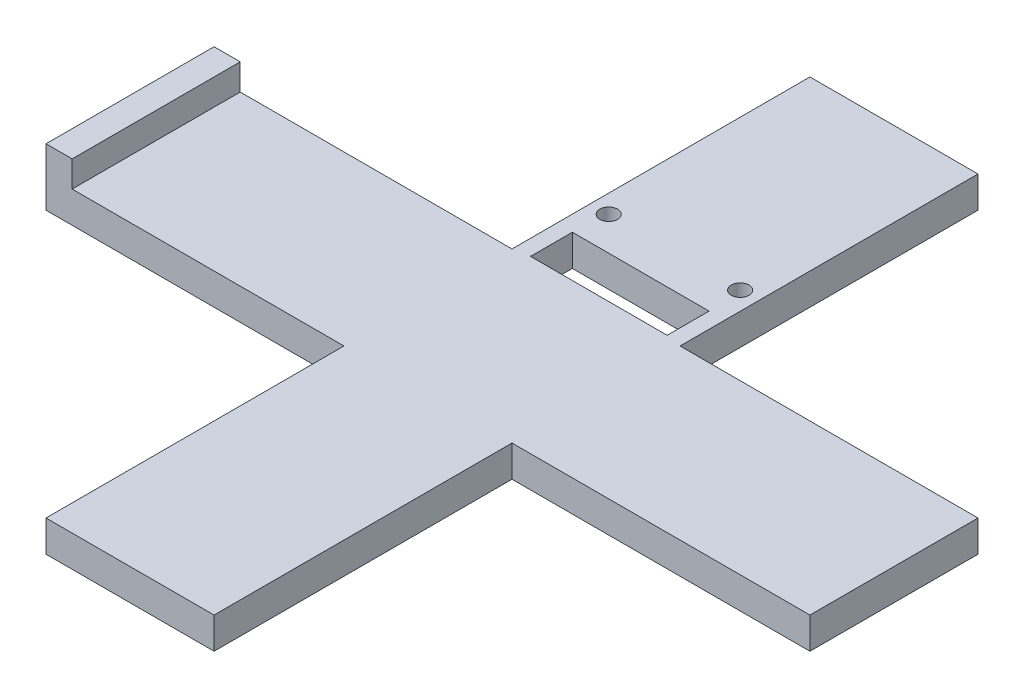
SolidWorks part; units mm, degrees
ref_plane "Front Plane" through (0, 0, 0) normal (0, 0, 1) x (1, 0, 0)
ref_plane "Top Plane" through (0, 0, 0) normal (0, 1, 0) x (1, 0, 0)
ref_plane "Right Plane" through (0, 0, 0) normal (1, 0, 0) x (0, 0, -1)
sketch "Sketch21" plane through (0, 0, 0) normal (0, 1, 0) x (1, 0, 0)
  line L22 (0, 73) -> (-16.06, 73)
  line L23 (-16.06, 73) -> (-16.06, 16.06)
  line L24 (-16.06, 16.06) -> (-73, 16.06)
  line L25 (-73, -16.06) -> (-16.06, -16.06)
  line L26 (-16.06, -16.06) -> (-16.06, -73)
  line L27 (-16.06, -73) -> (0, -73)
  line L28 (0, -73) -> (16.06, -73)
  line L29 (16.06, -73) -> (16.06, -16.06)
  line L30 (16.06, -16.06) -> (73, -16.06)
  line L31 (73, 16.06) -> (16.06, 16.06)
  line L32 (16.06, 16.06) -> (16.06, 73)
  line L33 (16.06, 73) -> (0, 73)
  line L34 (-73, 0) -> (-73, 16.06)
  line L35 (-73, -16.06) -> (-73, 0)
  line L36 (73, 0) -> (73, 16.06)
  line L37 (73, 0) -> (73, -16.06)
  line L38 (13.06, 16.6) -> (-13.06, 16.6)
  line L39 (13.06, 16.6) -> (13.06, 24.6)
  line L40 (13.06, 24.6) -> (-13.06, 24.6)
  line L41 (-13.06, 16.6) -> (-13.06, 24.6)
  line L42 (13.06, 16.6) -> (-13.06, 24.6) construction
  line L43 (13.06, 24.6) -> (-13.06, 16.6) construction
  circle A0 centre (-12.56, 31.04) radius 1.7
  circle A1 centre (12.56, 31.04) radius 1.7
  point P16 (0, 20.6)
  dimension "D7" = 3.4
  dimension "D9" = 12.56
  dimension "D10" = 6.44
  dimension "D1" = 56.94
  dimension "D2" = 16.06
  dimension "D3" = 26.12
  dimension "D4" = 8
  dimension "D5" = 0
  dimension "D6" = 24.6
  dimension "D8" = 12.56
  dimension "D11" = 6.44
  dimension "D13" = 16.06
extrude "Boss-Extrude18" add sketch "Sketch21" along normal blind 6
sketch "Sketch22" plane through (0, 6, 0) normal (0, 1, 0) x (1, 0, 0)
  line L0 (-73, -16.06) -> (-16.06, -16.06) construction
  line L1 (-73, 16.06) -> (-68, 16.06)
  line L2 (-73, 16.06) -> (-73, -16.06)
  line L3 (-73, -16.06) -> (-68, -16.06)
  line L4 (-68, 16.06) -> (-68, -16.06)
  dimension "D1" = 5
extrude "Boss-Extrude19" add sketch "Sketch22" along normal blind 5
